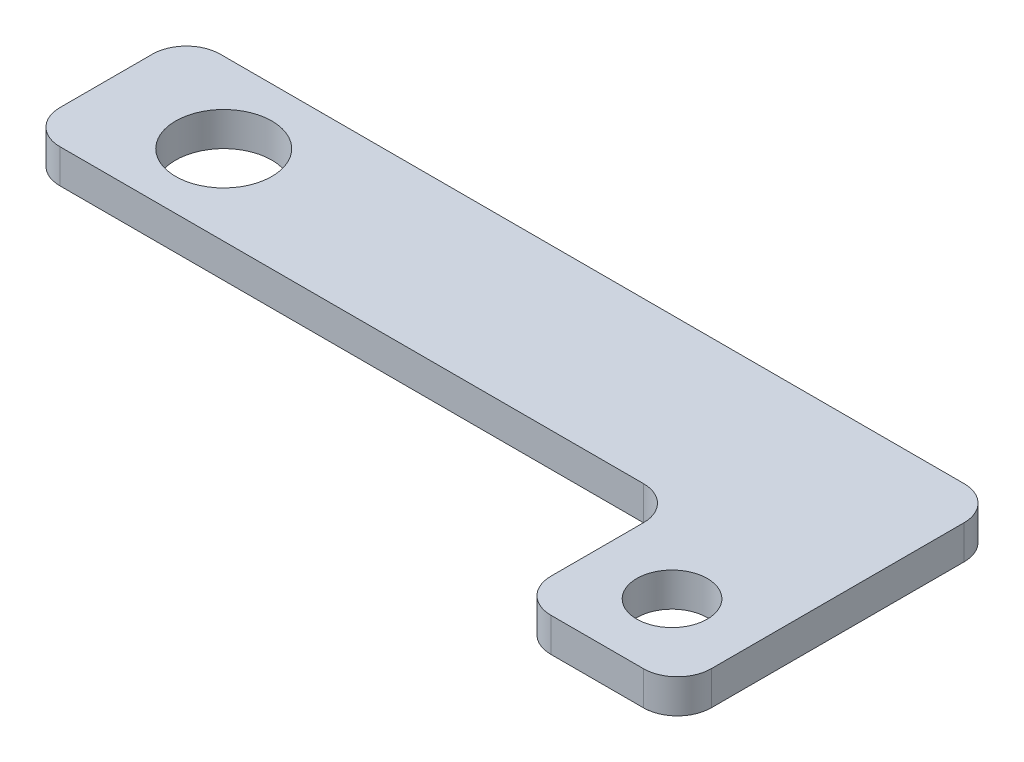
SolidWorks part; units mm, degrees
material "3003-H14"
ref_plane "X-Y Datum" through (0, 0, 0) normal (0, 0, 1) x (1, 0, 0)
ref_plane "X-Z Datum" through (0, 0, 0) normal (0, 1, 0) x (1, 0, 0)
ref_plane "Y-Z Datum" through (0, 0, 0) normal (1, 0, 0) x (0, 0, -1)
sketch "Sketch1" plane through (0, 0, 0) normal (0, 1, 0) x (1, 0, 0)
  line L0 (56, -44.0812) -> (71, -44.0812) construction
  line L1 (6.05, -36.0812) -> (6.05, -21.0812) construction
  line L2 (6.05, -36.0812) -> (56, -36.0812)
  line L3 (56, -36.0812) -> (56, -44.0812)
  line L4 (6.05, -21.0812) -> (71, -21.0812)
  line L5 (71, -21.0812) -> (71, -44.0812)
  line L6 (56, -44.0812) -> (56, -51.0812)
  line L7 (56, -51.0812) -> (71, -51.0812)
  line L8 (71, -51.0812) -> (71, -44.0812)
  line L9 (6.05, -21.0812) -> (-4.95, -21.0812)
  line L10 (-4.95, -21.0812) -> (-4.95, -36.0812)
  line L11 (-4.95, -36.0812) -> (6.05, -36.0812)
  point P0 (63.5, -44.0812)
  point P1 (6.05, -28.5812)
  point P7 (63.5, -44.0812)
  point P10 (6.05, -28.5812)
  point P18 (6.05, -28.5812)
  dimension "D1" = 15
  dimension "D2" = 15
  dimension "D3" = 11
  dimension "D4" = 7
extrude "Boss-Extrude1" add sketch "Sketch1" against normal blind 3.175
hole_wizard "M8 Clearance Hole1" positions "Sketch4" profile "Sketch3" hole size "M8" standard "ANSI Metric" end condition through all
sketch "Sketch4" plane through (0, -3.175, 0) normal (0, -1, 0) x (-1, 0, 0)
  point P0 (-6.05, -28.5812)
sketch "Sketch3" plane through (6.05, -3.175, 28.5812) normal (1, 0, 0) x (0, 0, -1)
  line L0 (0, 0) -> (0, 3.175)
  line L1 (0, 3.175) -> (4.5, 3.175)
  line L2 (4.5, 3.175) -> (4.5, 0)
  line L5 (4.5, 0) -> (0, 0)
  line L11 (0, -6.35) -> (0, 107.95) construction
  dimension "Thru Hole Dia." = 9
  dimension "Thru Hole Depth" = 3.175
hole_wizard "M6 Clearance Hole1" positions "Sketch7" profile "Sketch6" hole size "M6" standard "ANSI Metric" end condition through all
sketch "Sketch7" plane through (0, -3.175, 0) normal (0, -1, 0) x (-1, 0, 0)
  point P0 (-63.5, -44.0812)
sketch "Sketch6" plane through (63.5, -3.175, 44.0812) normal (1, 0, 0) x (0, 0, -1)
  line L0 (0, 0) -> (0, 3.175)
  line L1 (0, 3.175) -> (3.3, 3.175)
  line L2 (3.3, 3.175) -> (3.3, 0)
  line L5 (3.3, 0) -> (0, 0)
  line L11 (0, -6.35) -> (0, 107.95) construction
  dimension "Thru Hole Dia." = 6.6
  dimension "Thru Hole Depth" = 3.175
fillet "Fillet1" radius 3.175 6 edges at (71, -1.5875, 21.0812) (-4.95, -1.5875, 21.0812) (-4.95, -1.5875, 36.0812) (56, -1.5875, 36.0812) (71, -1.5875, 51.0812) (56, -1.5875, 51.0812)
